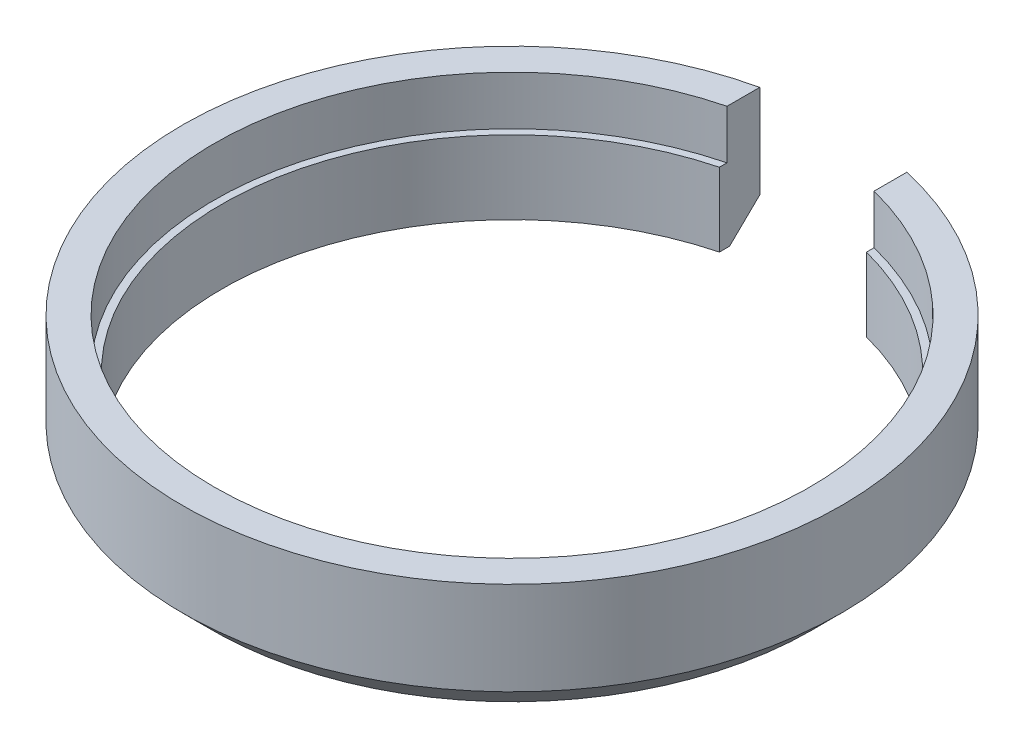
SolidWorks part; units mm, degrees
ref_plane "Front" through (0, 0, 0) normal (0, 0, 1) x (1, 0, 0)
ref_plane "Top" through (0, 0, 0) normal (0, 1, 0) x (1, 0, 0)
ref_plane "Right" through (0, 0, 0) normal (1, 0, 0) x (0, 0, -1)
sketch "Эскиз1" plane through (0, 0, 0) normal (0, 0, 1) x (1, 0, 0)
  line L0 (0, 0) -> (0, 5) construction
  line L1 (-11.85, 0) -> (-13.45, 0)
  line L2 (-13.45, 0) -> (-13.45, 5)
  line L3 (-13.45, 5) -> (-12.15, 5)
  line L4 (-12.15, 5) -> (-12.15, 3)
  line L5 (-12.15, 3) -> (-11.85, 3)
  line L6 (-11.85, 3) -> (-11.85, 0)
  dimension "D1" = 5
  dimension "D2" = 26.9
  dimension "D3" = 24.3
  dimension "D4" = 2
  dimension "D5" = 0.3
revolve "Повернуть1" add sketch "Эскиз1" angle 360 about L0
chamfer "Фаска1" distance 1.2 angle 45 1 edges at (0, 0, -13.45)
sketch "Эскиз2" plane through (0, 5, 0) normal (0, 1, 0) x (1, 0, 0)
  line L1 (-3, 17) -> (3, 17)
  line L2 (-3, 17) -> (-3, 7)
  line L3 (-3, 7) -> (3, 7)
  line L4 (3, 17) -> (3, 7)
  dimension "D1" = 6
  dimension "D2" = 3
  dimension "D3" = 7
  dimension "D4" = 10
extrude "Вырез-Вытянуть1" cut sketch "Эскиз2" against normal up to next
